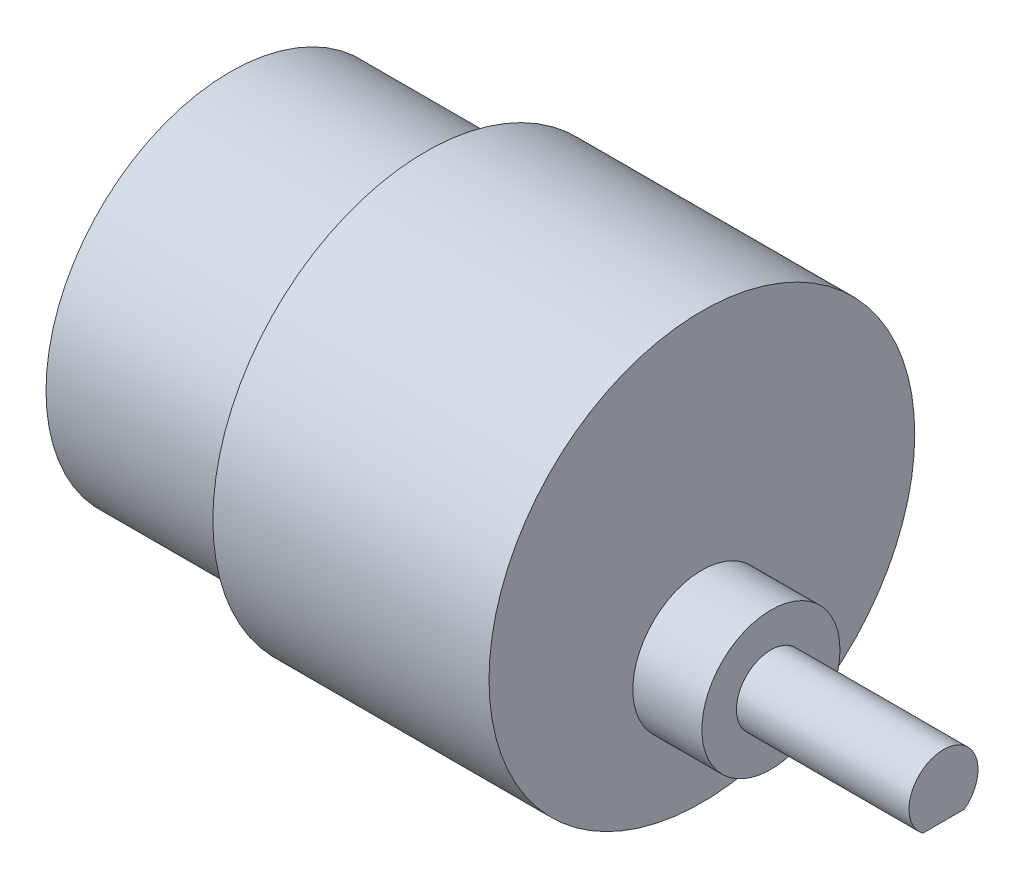
SolidWorks part; units mm, degrees
ref_plane "Front Plane" through (0, 0, 0) normal (0, 0, 1) x (1, 0, 0)
ref_plane "Top Plane" through (0, 0, 0) normal (0, 1, 0) x (1, 0, 0)
ref_plane "Right Plane" through (0, 0, 0) normal (1, 0, 0) x (0, 0, -1)
sketch "Sketch1" plane through (0, 0, 0) normal (1, 0, 0) x (0, 0, -1)
  circle A0 centre (0, 0) radius 18.5
  dimension "D1" = 37
extrude "Boss-Extrude1" add sketch "Sketch1" along normal blind 24
sketch "Sketch2" plane through (0, 0, 0) normal (-1, 0, 0) x (0, 0, 1)
  circle A0 centre (0, 0) radius 16
  dimension "D1" = 32
extrude "Boss-Extrude2" add sketch "Sketch2" along normal blind 17
sketch "Sketch4" plane through (24, 0, 0) normal (1, 0, 0) x (0, 0, -1)
  line L0 (0, -7) -> (0, 0) construction
  circle A0 centre (0, -7) radius 6
  dimension "D1" = 12
  dimension "D2" = 7
extrude "Boss-Extrude3" add sketch "Sketch4" along normal blind 6
sketch "Sketch5" plane through (30, 0, 0) normal (1, 0, 0) x (0, 0, -1)
  circle A0 centre (0, -7) radius 3
  dimension "D1" = 6
extrude "Boss-Extrude4" add sketch "Sketch5" along normal blind 15
sketch "Sketch6" plane through (45, 0, 0) normal (1, 0, 0) x (0, 0, -1)
  line L0 (0, -4) -> (0, -9.4) construction
  line L1 (-3.5914, -9.4) -> (2.8657, -9.4)
  line L2 (-3.5914, -9.4) -> (-3.5914, -11.8035)
  line L3 (-3.5914, -11.8035) -> (2.8657, -11.8035)
  line L4 (2.8657, -9.4) -> (2.8657, -11.8035)
  circle A0 centre (0, -7) radius 3 construction
  circle A1 centre (0, -7) radius 3 construction
  point P9 (2.8657, -9.4)
  dimension "D1" = 5.4
extrude "Cut-Extrude1" cut sketch "Sketch6" against normal blind 11
sketch "Sketch7" plane through (-17, 0, 0) normal (-1, 0, 0) x (0, 0, 1)
  circle A0 centre (0, 0) radius 3.75
  dimension "D1" = 7.5
extrude "Boss-Extrude5" add sketch "Sketch7" along normal blind 5.5
